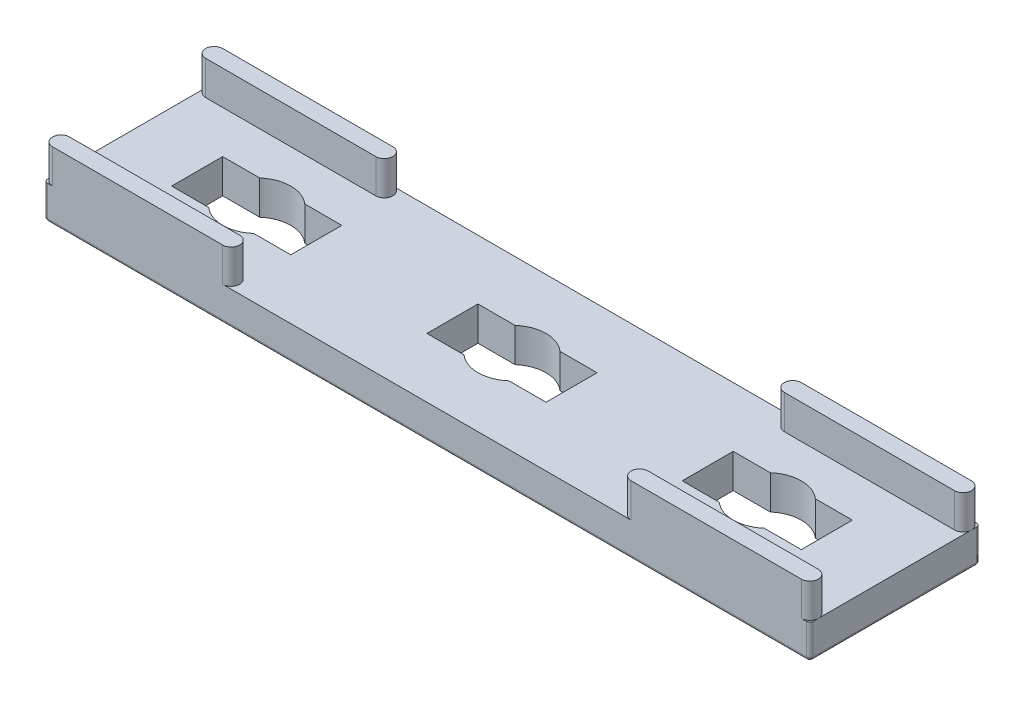
SolidWorks part; units mm, degrees
ref_plane "前视基准面" through (0, 0, 0) normal (0, 0, 1) x (1, 0, 0)
ref_plane "上视基准面" through (0, 0, 0) normal (0, 1, 0) x (1, 0, 0)
ref_plane "右视基准面" through (0, 0, 0) normal (1, 0, 0) x (0, 0, -1)
sketch "草图1" plane through (0, 0, 0) normal (0, 1, 0) x (1, 0, 0)
  line L0 (22.5, 5) -> (22.5, -5)
  line L1 (22.5, 5) -> (-22.5, 5)
  line L2 (22.5, -5) -> (-22.5, -5)
  line L3 (-22.5, 5) -> (-22.5, -5)
  line L4 (22.5, 5) -> (-22.5, -5) construction
  line L5 (22.5, -5) -> (-22.5, 5) construction
  point P1 (0, 0)
  dimension "D1" = 10
  dimension "D2" = 45
extrude "凸台-拉伸1" add sketch "草图1" along normal blind 2
sketch "草图2" plane through (0, 2, 0) normal (0, 1, 0) x (1, 0, 0)
  line L0 (-22.5, 5) -> (-22, 5) construction
  line L1 (22.5, 5) -> (-22.5, 5) construction
  line L2 (-22, 5) -> (-22, 4.5) construction
  line L3 (-22, 4.5) -> (-12, 4.5) construction
  line L4 (-22, 4) -> (-12, 4)
  line L5 (-22, 5) -> (-12, 5)
  arc A0 (-22, 5) -> (-22, 4) centre (-22, 4.5) ccw
  arc A1 (-12, 4) -> (-12, 5) centre (-12, 4.5) ccw
  dimension "D4" = 1
  dimension "D1" = 0.5
  dimension "D2" = 0.5
  dimension "D3" = 10
extrude "凸台-拉伸2" add sketch "草图2" along normal blind 2
mirror "镜向1" about plane through (0, 0, 0) normal (0, 0, 1) of "凸台-拉伸2"
mirror "镜向2" about plane through (0, 0, 0) normal (1, 0, 0) of "凸台-拉伸2", "镜向1"
sketch "草图3" plane through (0, 2, 0) normal (0, 1, 0) x (1, 0, 0)
  line L0 (3.5, 1.5) -> (3.5, -1.5)
  line L1 (3.5, 1.5) -> (1.3229, 1.5)
  line L2 (3.5, -1.5) -> (1.3229, -1.5)
  line L3 (-3.5, 1.5) -> (-3.5, -1.5)
  line L4 (3.5, 1.5) -> (-3.5, -1.5) construction
  line L5 (3.5, -1.5) -> (-3.5, 1.5) construction
  line L6 (-1.3229, 1.5) -> (-3.5, 1.5)
  line L7 (-1.3229, -1.5) -> (-3.5, -1.5)
  arc A0 (-1.3229, -1.5) -> (1.3229, -1.5) centre (0, 0) ccw
  arc A1 (1.3229, 1.5) -> (-1.3229, 1.5) centre (0, 0) ccw
  dimension "D1" = 4
  dimension "D2" = 7
  dimension "D3" = 3
extrude "切除-拉伸1" cut sketch "草图3" against normal up to next
sketch "草图4" plane through (0, 2, 0) normal (0, 1, 0) x (1, 0, 0)
  line L0 (-15, 0) -> (0, 0) construction
  line L1 (-11.5, 1.5) -> (-11.5, -1.5)
  line L2 (-11.5, 1.5) -> (-13.6771, 1.5)
  line L3 (-11.5, -1.5) -> (-13.6771, -1.5)
  line L4 (-18.5, 1.5) -> (-18.5, -1.5)
  line L5 (-11.5, 1.5) -> (-18.5, -1.5) construction
  line L6 (-11.5, -1.5) -> (-18.5, 1.5) construction
  line L7 (-16.3229, 1.5) -> (-18.5, 1.5)
  line L8 (-16.3229, -1.5) -> (-18.5, -1.5)
  arc A0 (-16.3229, -1.5) -> (-13.6771, -1.5) centre (-15, 0) ccw
  arc A1 (-13.6771, 1.5) -> (-16.3229, 1.5) centre (-15, 0) ccw
  dimension "D2" = 4
  dimension "D3" = 7
  dimension "D4" = 3
extrude "切除-拉伸2" cut sketch "草图4" against normal up to next
mirror "镜向3" about plane through (0, 0, 0) normal (1, 0, 0) of "切除-拉伸2"
fillet "圆角1" radius 0.2 8 edges at (0, 0, 5) (-22.5, 1, 5) (-22.5, 0, 0) (-22.5, 1, -5) (0, 0, -5) (22.5, 0, 0) (22.5, 1, -5) (22.5, 1, 5)
